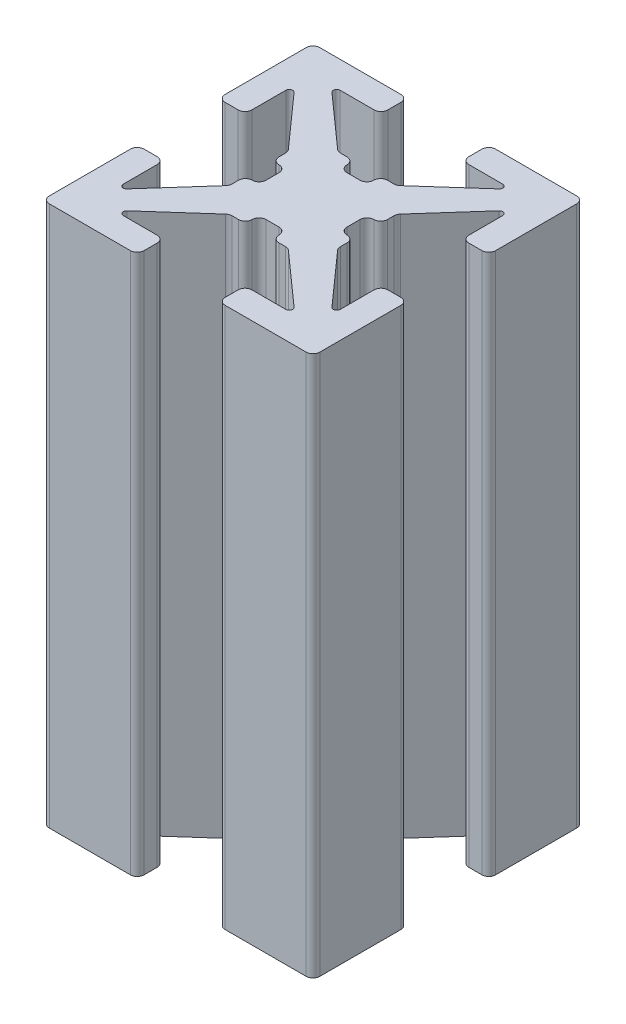
SolidWorks part; units mm, degrees
material "6063-T6"
ref_plane "Front Plane" through (0, 0, 0) normal (0, 0, 1) x (1, 0, 0)
ref_plane "Top Plane" through (0, 0, 0) normal (0, 1, 0) x (1, 0, 0)
ref_plane "Right Plane" through (0, 0, 0) normal (1, 0, 0) x (0, 0, -1)
sketch "Sketch1" plane through (0, 0, 0) normal (0, 1, 0) x (1, 0, 0)
  line L0 (-1.1595, 2.0709) -> (-3.0909, 3.7914)
  line L1 (-0.7493, 2.0066) -> (-0.9906, 2.0066)
  line L2 (-1.4986, 4.2672) -> (-1.4986, 4.7498)
  line L3 (-1.7526, 4.0132) -> (-3.0064, 4.0132)
  line L4 (-1.7526, 5.0038) -> (-4.7498, 5.0038)
  line L5 (-0.2413, 1.4986) -> (0.2413, 1.4986)
  line L6 (-5.0038, 5.0038) -> (5.0038, -5.0038) construction
  line L7 (-1.4986, 0.2413) -> (-1.4986, -0.2413)
  line L8 (-5.0038, 1.7526) -> (-5.0038, 4.7498)
  line L9 (-4.0132, 1.7526) -> (-4.0132, 3.0064)
  line L10 (-4.2672, 1.4986) -> (-4.7498, 1.4986)
  line L11 (-2.0066, 0.7493) -> (-2.0066, 0.9906)
  line L12 (0, 5.0038) -> (0, -5.0038) construction
  line L13 (5.0038, 0) -> (-5.0038, 0) construction
  line L14 (-2.0709, 1.1595) -> (-3.7914, 3.0909)
  line L15 (2.0709, 1.1595) -> (3.7914, 3.0909)
  line L16 (2.0066, 0.7493) -> (2.0066, 0.9906)
  line L17 (4.2672, 1.4986) -> (4.7498, 1.4986)
  line L18 (4.0132, 1.7526) -> (4.0132, 3.0064)
  line L19 (5.0038, 1.7526) -> (5.0038, 4.7498)
  line L20 (1.4986, 0.2413) -> (1.4986, -0.2413)
  line L21 (1.7526, 5.0038) -> (4.7498, 5.0038)
  line L22 (1.7526, 4.0132) -> (3.0064, 4.0132)
  line L23 (1.4986, 4.2672) -> (1.4986, 4.7498)
  line L24 (0.7493, 2.0066) -> (0.9906, 2.0066)
  line L25 (1.1595, 2.0709) -> (3.0909, 3.7914)
  line L26 (1.1595, -2.0709) -> (3.0909, -3.7914)
  line L27 (0.7493, -2.0066) -> (0.9906, -2.0066)
  line L28 (1.4986, -4.2672) -> (1.4986, -4.7498)
  line L29 (1.7526, -4.0132) -> (3.0064, -4.0132)
  line L30 (1.7526, -5.0038) -> (4.7498, -5.0038)
  line L31 (5.0038, -1.7526) -> (5.0038, -4.7498)
  line L32 (4.0132, -1.7526) -> (4.0132, -3.0064)
  line L33 (4.2672, -1.4986) -> (4.7498, -1.4986)
  line L34 (2.0066, -0.7493) -> (2.0066, -0.9906)
  line L35 (2.0709, -1.1595) -> (3.7914, -3.0909)
  line L36 (-2.0709, -1.1595) -> (-3.7914, -3.0909)
  line L37 (-2.0066, -0.7493) -> (-2.0066, -0.9906)
  line L38 (-4.2672, -1.4986) -> (-4.7498, -1.4986)
  line L39 (-4.0132, -1.7526) -> (-4.0132, -3.0064)
  line L40 (-5.0038, -1.7526) -> (-5.0038, -4.7498)
  line L41 (-0.2413, -1.4986) -> (0.2413, -1.4986)
  line L42 (-1.7526, -5.0038) -> (-4.7498, -5.0038)
  line L43 (-1.7526, -4.0132) -> (-3.0064, -4.0132)
  line L44 (-1.4986, -4.2672) -> (-1.4986, -4.7498)
  line L45 (-0.7493, -2.0066) -> (-0.9906, -2.0066)
  line L46 (-1.1595, -2.0709) -> (-3.0909, -3.7914)
  arc A0 (-4.0132, 3.0064) -> (-3.7914, 3.0909) centre (-3.8862, 3.0064) cw
  arc A1 (-1.7526, 0.4953) -> (-2.0066, 0.7493) centre (-1.7526, 0.7493) cw
  arc A2 (-2.0066, 0.9906) -> (-2.0709, 1.1595) centre (-2.2606, 0.9906) ccw
  arc A3 (-4.0132, 1.7526) -> (-4.2672, 1.4986) centre (-4.2672, 1.7526) cw
  arc A4 (-4.7498, 1.4986) -> (-5.0038, 1.7526) centre (-4.7498, 1.7526) cw
  arc A5 (-1.4986, 0.2413) -> (-1.7526, 0.4953) centre (-1.7526, 0.2413) ccw
  arc A6 (-0.2413, 1.4986) -> (-0.4953, 1.7526) centre (-0.2413, 1.7526) cw
  arc A7 (-1.4986, 4.7498) -> (-1.7526, 5.0038) centre (-1.7526, 4.7498) ccw
  arc A8 (-1.7526, 4.0132) -> (-1.4986, 4.2672) centre (-1.7526, 4.2672) ccw
  arc A9 (-0.9906, 2.0066) -> (-1.1595, 2.0709) centre (-0.9906, 2.2606) cw
  arc A10 (-0.4953, 1.7526) -> (-0.7493, 2.0066) centre (-0.7493, 1.7526) ccw
  arc A11 (-3.0064, 4.0132) -> (-3.0909, 3.7914) centre (-3.0064, 3.8862) ccw
  arc A12 (4.7498, 5.0038) -> (5.0038, 4.7498) centre (4.7498, 4.7498) cw
  arc A13 (3.0064, 4.0132) -> (3.0909, 3.7914) centre (3.0064, 3.8862) cw
  arc A14 (0.4953, 1.7526) -> (0.7493, 2.0066) centre (0.7493, 1.7526) cw
  arc A15 (0.9906, 2.0066) -> (1.1595, 2.0709) centre (0.9906, 2.2606) ccw
  arc A16 (1.7526, 4.0132) -> (1.4986, 4.2672) centre (1.7526, 4.2672) cw
  arc A17 (1.4986, 4.7498) -> (1.7526, 5.0038) centre (1.7526, 4.7498) cw
  arc A18 (0.2413, 1.4986) -> (0.4953, 1.7526) centre (0.2413, 1.7526) ccw
  arc A19 (1.4986, 0.2413) -> (1.7526, 0.4953) centre (1.7526, 0.2413) cw
  arc A20 (4.7498, 1.4986) -> (5.0038, 1.7526) centre (4.7498, 1.7526) ccw
  arc A21 (4.0132, 1.7526) -> (4.2672, 1.4986) centre (4.2672, 1.7526) ccw
  arc A22 (2.0066, 0.9906) -> (2.0709, 1.1595) centre (2.2606, 0.9906) cw
  arc A23 (1.7526, 0.4953) -> (2.0066, 0.7493) centre (1.7526, 0.7493) ccw
  arc A24 (4.0132, 3.0064) -> (3.7914, 3.0909) centre (3.8862, 3.0064) ccw
  arc A25 (-4.7498, -5.0038) -> (-5.0038, -4.7498) centre (-4.7498, -4.7498) cw
  arc A26 (4.0132, -3.0064) -> (3.7914, -3.0909) centre (3.8862, -3.0064) cw
  arc A27 (1.7526, -0.4953) -> (2.0066, -0.7493) centre (1.7526, -0.7493) cw
  arc A28 (2.0066, -0.9906) -> (2.0709, -1.1595) centre (2.2606, -0.9906) ccw
  arc A29 (4.0132, -1.7526) -> (4.2672, -1.4986) centre (4.2672, -1.7526) cw
  arc A30 (4.7498, -1.4986) -> (5.0038, -1.7526) centre (4.7498, -1.7526) cw
  arc A31 (1.4986, -0.2413) -> (1.7526, -0.4953) centre (1.7526, -0.2413) ccw
  arc A32 (0.2413, -1.4986) -> (0.4953, -1.7526) centre (0.2413, -1.7526) cw
  arc A33 (1.4986, -4.7498) -> (1.7526, -5.0038) centre (1.7526, -4.7498) ccw
  arc A34 (1.7526, -4.0132) -> (1.4986, -4.2672) centre (1.7526, -4.2672) ccw
  arc A35 (0.9906, -2.0066) -> (1.1595, -2.0709) centre (0.9906, -2.2606) cw
  arc A36 (0.4953, -1.7526) -> (0.7493, -2.0066) centre (0.7493, -1.7526) ccw
  arc A37 (3.0064, -4.0132) -> (3.0909, -3.7914) centre (3.0064, -3.8862) ccw
  arc A38 (4.7498, -5.0038) -> (5.0038, -4.7498) centre (4.7498, -4.7498) ccw
  arc A39 (-3.0064, -4.0132) -> (-3.0909, -3.7914) centre (-3.0064, -3.8862) cw
  arc A40 (-0.4953, -1.7526) -> (-0.7493, -2.0066) centre (-0.7493, -1.7526) cw
  arc A41 (-0.9906, -2.0066) -> (-1.1595, -2.0709) centre (-0.9906, -2.2606) ccw
  arc A42 (-1.7526, -4.0132) -> (-1.4986, -4.2672) centre (-1.7526, -4.2672) cw
  arc A43 (-1.4986, -4.7498) -> (-1.7526, -5.0038) centre (-1.7526, -4.7498) cw
  arc A44 (-0.2413, -1.4986) -> (-0.4953, -1.7526) centre (-0.2413, -1.7526) ccw
  arc A45 (-1.4986, -0.2413) -> (-1.7526, -0.4953) centre (-1.7526, -0.2413) cw
  arc A46 (-4.7498, -1.4986) -> (-5.0038, -1.7526) centre (-4.7498, -1.7526) ccw
  arc A47 (-4.0132, -1.7526) -> (-4.2672, -1.4986) centre (-4.2672, -1.7526) ccw
  arc A48 (-2.0066, -0.9906) -> (-2.0709, -1.1595) centre (-2.2606, -0.9906) cw
  arc A49 (-1.7526, -0.4953) -> (-2.0066, -0.7493) centre (-1.7526, -0.7493) ccw
  arc A50 (-4.0132, -3.0064) -> (-3.7914, -3.0909) centre (-3.8862, -3.0064) ccw
  arc A51 (-4.7498, 5.0038) -> (-5.0038, 4.7498) centre (-4.7498, 4.7498) ccw
  point P0 (0, 0)
  point P81 (-1.4986, 0)
  point P82 (0, 1.4986)
  point P156 (1.4986, 0)
  dimension "D1" = 5.0038
  dimension "D2" = 0.9906
  dimension "D3" = 1.4986
  dimension "D8" = 0.254
  dimension "D9" = 0.127
  dimension "D5" = 0.508
  dimension "D6" = 1.4986
  dimension "D7" = 0.4953
  dimension "D10" = 0.4953
  dimension "D11" = 0.9906
extrude "Boss-Extrude1" add sketch "Sketch1" along normal blind 20
